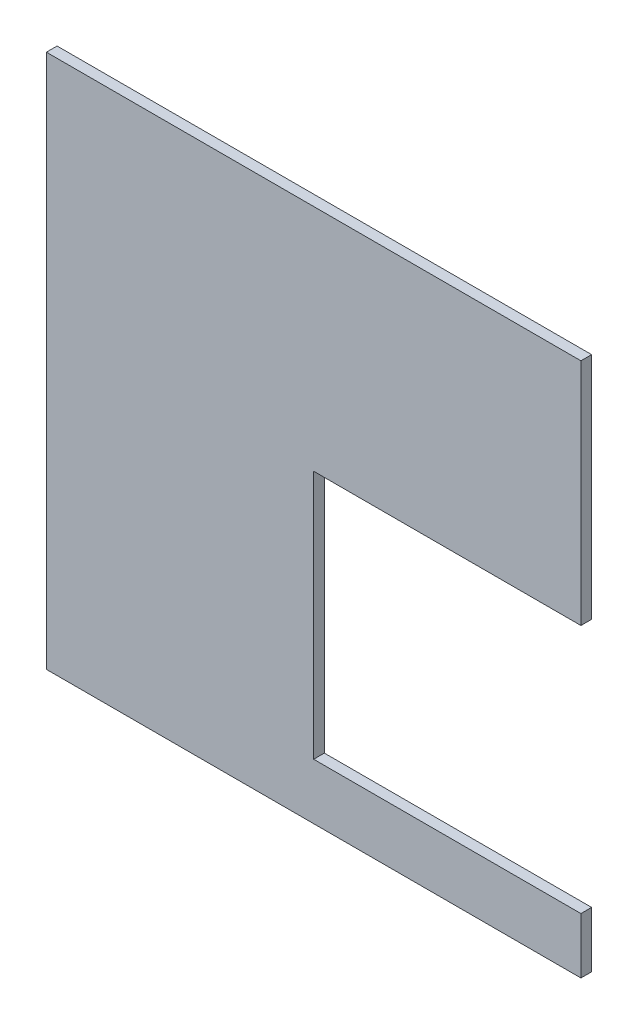
SolidWorks part; units mm, degrees
ref_plane "Plan de face" through (0, 0, 0) normal (0, 0, 1) x (1, 0, 0)
ref_plane "Plan de dessus" through (0, 0, 0) normal (0, 1, 0) x (1, 0, 0)
ref_plane "Plan de droite" through (0, 0, 0) normal (1, 0, 0) x (0, 0, -1)
sketch "Esquisse1" plane through (0, 0, 0) normal (0, 0, 1) x (1, 0, 0)
  line L1 (75, -75) -> (-75, -75)
  line L2 (75, -75) -> (75, 75)
  line L3 (75, 75) -> (-75, 75)
  line L4 (-75, -75) -> (-75, 75)
  line L5 (75, -75) -> (-75, 75) construction
  line L6 (75, 75) -> (-75, -75) construction
  point P0 (0, 0)
  dimension "D1" = 150
  dimension "D2" = 150
extrude "Boss.-Extru.1" add sketch "Esquisse1" along normal blind 3
sketch "Esquisse2" plane through (0, 0, 3) normal (0, 0, 1) x (1, 0, 0)
  line L0 (21.8299, -64.338) -> (26.8299, -64.338) construction
  line L1 (0, 10.662) -> (75, 10.662)
  line L2 (0, 10.662) -> (0, -59.338)
  line L3 (0, -59.338) -> (75, -59.338)
  line L4 (75, 10.662) -> (75, -59.338)
  line L5 (0, 10.662) -> (75, -59.338) construction
  line L6 (0, -59.338) -> (75, 10.662) construction
  line L8 (61.8299, 15.662) -> (56.8299, 15.662) construction
  line L9 (75, -75) -> (75, 75) construction
  point P0 (37.5, -24.338)
  dimension "D1" = 5
  dimension "D2" = 75
  dimension "D3" = 5
extrude "Enlèv. mat.-Extru.1" cut sketch "Esquisse2" against normal through all
